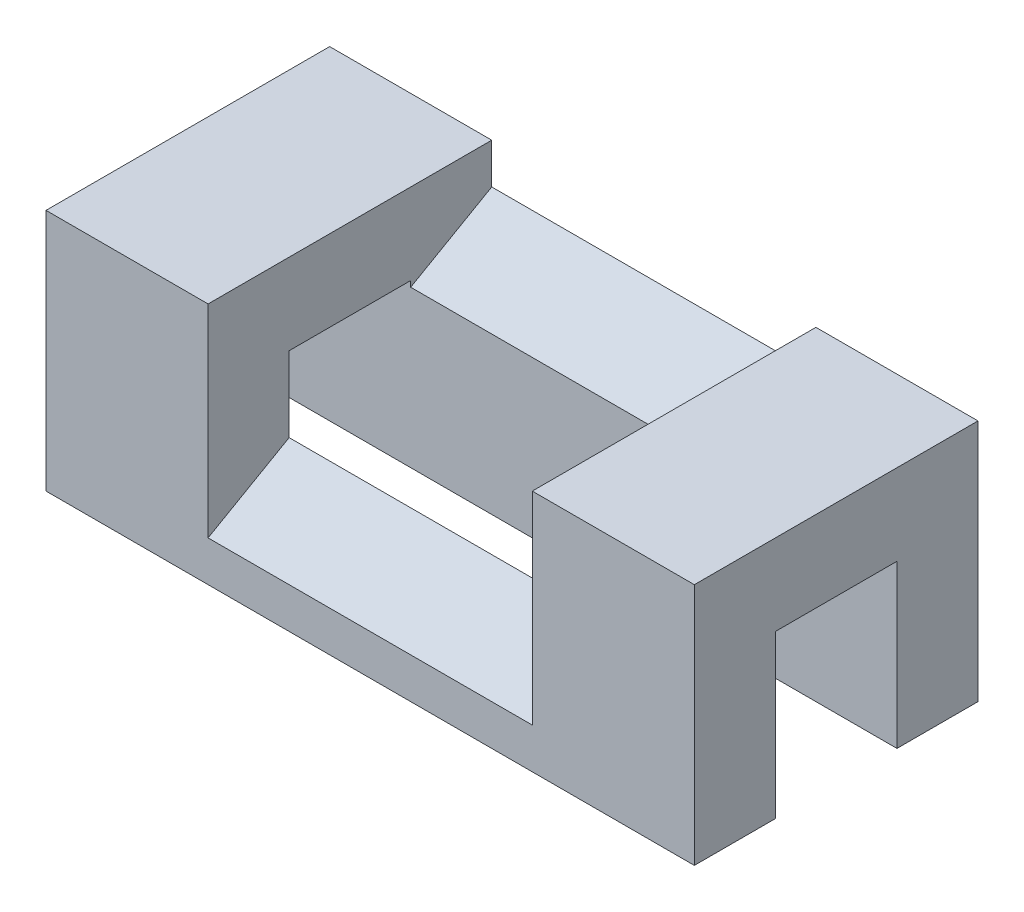
SolidWorks part; units mm, degrees
ref_plane "前基準面" through (0, 0, 0) normal (0, 0, 1) x (1, 0, 0)
ref_plane "上基準面" through (0, 0, 0) normal (0, 1, 0) x (1, 0, 0)
ref_plane "右基準面" through (0, 0, 0) normal (1, 0, 0) x (0, 0, -1)
sketch "草圖1" plane through (0, 0, 0) normal (1, 0, 0) x (0, 0, -1)
  line L0 (0, 0) -> (-63.4859, 0) construction
  line L1 (0, 0) -> (0, 55.8109) construction
  line L3 (-17.5, 15) -> (17.5, 15)
  line L4 (-17.5, 15) -> (-17.5, -15)
  line L5 (-17.5, -15) -> (17.5, -15)
  line L6 (17.5, 15) -> (17.5, -15)
  dimension "D1" = 35
  dimension "D2" = 30
extrude "填料-伸長1" add sketch "草圖1" along normal mid plane 80
sketch "草圖3" plane through (0, 0, 0) normal (1, 0, 0) x (0, 0, -1)
  line L0 (-7.5, -15) -> (-7.5, 5)
  line L1 (-7.5, 5) -> (7.5, 5)
  line L2 (7.5, 5) -> (7.5, -15)
  line L4 (-17.5, 15) -> (-17.5, -15)
  line L5 (-17.5, -15) -> (17.5, -15)
  line L6 (17.5, -15) -> (17.5, 15)
  line L7 (17.5, 15) -> (-17.5, 15)
  line L8 (-17.5, 15) -> (-17.5, -15)
  line L9 (-17.5, -15) -> (-7.5, -15)
  line L10 (17.5, -15) -> (17.5, 15)
  line L11 (17.5, 15) -> (-17.5, 15)
  line L12 (-7.5, -15) -> (7.5, -15)
  line L13 (7.5, -15) -> (17.5, -15)
  dimension "D2" = 10
  dimension "D3" = 10
  dimension "D4" = 20
  dimension "D1" = 0
extrude "除料-伸長1" cut sketch "草圖3" against normal mid plane 140 contours L0 L12 L2 L1
sketch "草圖5" plane through (0, 0, 0) normal (1, 0, 0) x (0, 0, -1)
  line L0 (17.5, 10) -> (-17.5, -10)
  line L8 (-17.5, -15) -> (-7.5, -15)
  line L9 (-7.5, -15) -> (-7.5, 5)
  line L10 (-7.5, 5) -> (7.5, 5)
  line L11 (7.5, 5) -> (7.5, -15)
  line L12 (7.5, -15) -> (17.5, -15)
  line L13 (17.5, -15) -> (17.5, 15)
  line L14 (17.5, 15) -> (-17.5, 15)
  line L15 (-17.5, 15) -> (-17.5, -15)
  line L16 (-17.5, -15) -> (-7.5, -15)
  line L17 (-7.5, -15) -> (-7.5, 5)
  line L18 (-7.5, 5) -> (7.5, 5)
  line L19 (7.5, 5) -> (7.5, -15)
  line L20 (7.5, -15) -> (17.5, -15)
  line L21 (17.5, -15) -> (17.5, 15)
  line L22 (17.5, 15) -> (-17.5, 15)
  line L23 (-17.5, 15) -> (-17.5, -15)
  dimension "D2" = 5
  dimension "D3" = 5
  dimension "D1" = 0
extrude "除料-伸長3" cut sketch "草圖5" against normal mid plane 40 contours L22 L23 L0 L17 L18 L19 L21
